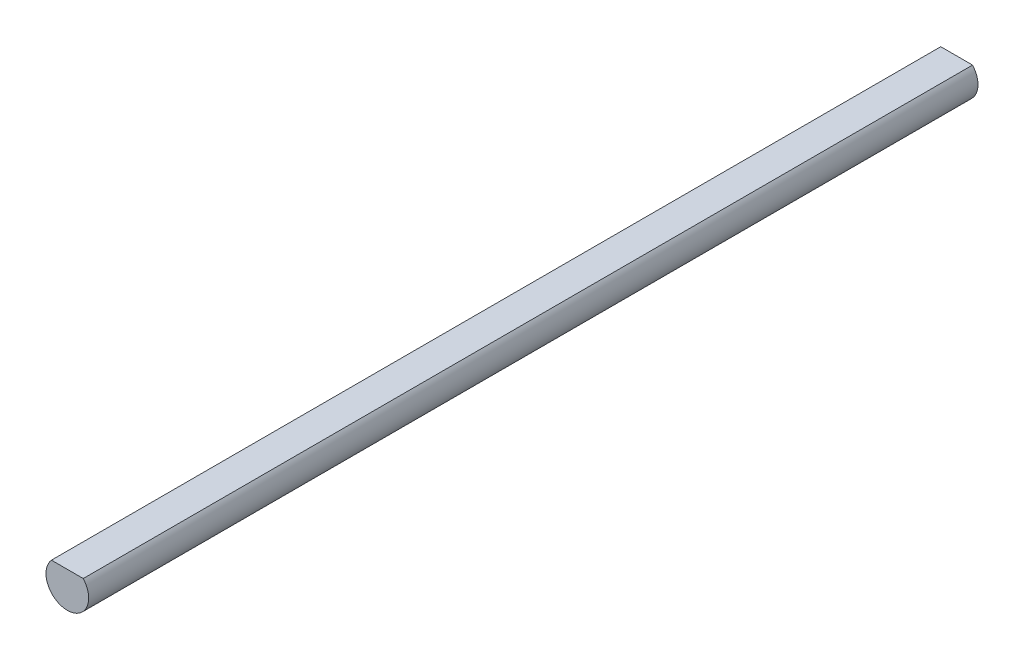
SolidWorks part; units mm, degrees
ref_plane "前基準面" through (0, 0, 0) normal (0, 0, 1) x (1, 0, 0)
ref_plane "上基準面" through (0, 0, 0) normal (0, 1, 0) x (1, 0, 0)
ref_plane "右基準面" through (0, 0, 0) normal (1, 0, 0) x (0, 0, -1)
sketch "草圖1" plane through (0, 0, 0) normal (1, 0, 0) x (0, 0, -1)
  line L1 (-62.5, 3) -> (62.5, 3)
  line L2 (-62.5, 3) -> (-62.5, 0)
  line L3 (-62.5, 0) -> (62.5, 0)
  line L4 (62.5, 3) -> (62.5, 0)
  point P4 (0, 0)
  dimension "D1" = 125
  dimension "D2" = 3
revolve "旋轉1" add sketch "草圖1" angle 360 about L3
sketch "草圖3" plane through (0, 0, 0) normal (0, 0, 1) x (1, 0, 0)
  line L1 (-5.4144, 3.8979) -> (6.426, 3.8979)
  line L2 (-5.4144, 3.8979) -> (-5.4144, 2)
  line L3 (-5.4144, 2) -> (6.426, 2)
  line L4 (6.426, 3.8979) -> (6.426, 2)
  dimension "D1" = 2
extrude "除料-伸長1" cut sketch "草圖3" against normal through all both and the other way through all contours L1 L4 L3 L2
